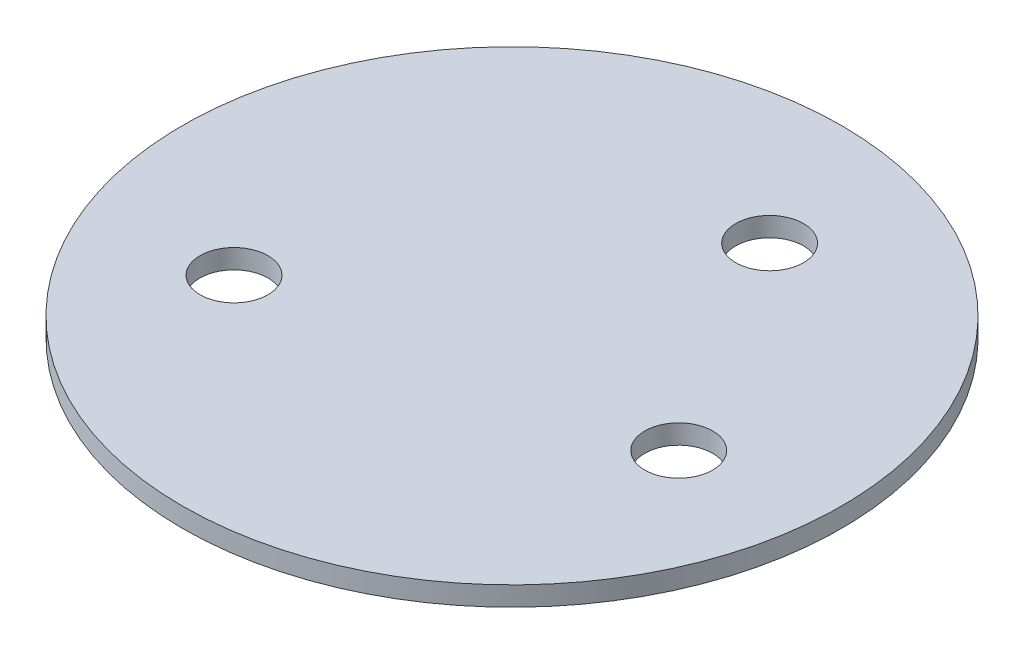
SolidWorks part; units mm, degrees
ref_plane "Front Plane" through (0, 0, 0) normal (0, 0, 1) x (1, 0, 0)
ref_plane "Top Plane" through (0, 0, 0) normal (0, 1, 0) x (1, 0, 0)
ref_plane "Right Plane" through (0, 0, 0) normal (1, 0, 0) x (0, 0, -1)
sketch "Sketch1" plane through (0, 0, 0) normal (0, -1, 0) x (1, 0, 0)
  circle A0 centre (1034.9634, -1081.3254) radius 11.1125 construction
  circle A1 centre (991.0175, -1155.0493) radius 11.1125 construction
  circle A2 centre (912.393, -1058.2224) radius 11.1125 construction
  circle A3 centre (1034.9634, -1081.3254) radius 11.1125
  circle A4 centre (991.0175, -1155.0493) radius 11.1125
  circle A5 centre (912.393, -1058.2224) radius 11.1125
  arc A6 (1034.9634, -1081.3254) -> (991.0175, -1155.0493) centre (969.4454, -1092.2307) ccw construction
  circle A7 centre (969.4454, -1092.2307) radius 107.95
  dimension "D1" = 215.9
extrude "Boss-Extrude1" add sketch "Sketch1" along normal blind 6.35
